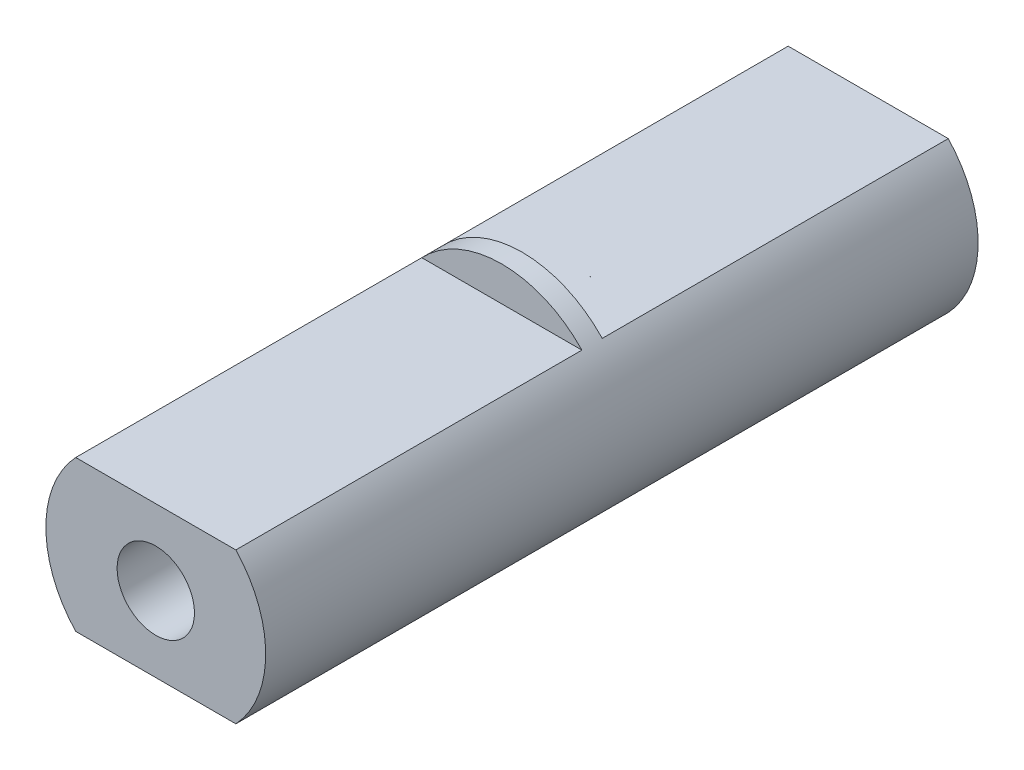
SolidWorks part; units mm, degrees
ref_plane "Front Plane" through (0, 0, 0) normal (0, 0, 1) x (1, 0, 0)
ref_plane "Top Plane" through (0, 0, 0) normal (0, 1, 0) x (1, 0, 0)
ref_plane "Right Plane" through (0, 0, 0) normal (1, 0, 0) x (0, 0, -1)
sketch "Sketch2" plane through (0, 0, 0) normal (0, 0, 1) x (1, 0, 0)
  line L0 (0, 1.85) -> (0, -1.85)
  line L1 (-1.9666, 1.85) -> (1.9666, 1.85)
  line L2 (1.9666, -1.85) -> (-1.9666, -1.85)
  arc A0 (-1.9666, 1.85) -> (-1.9666, -1.85) centre (0, 0) ccw
  circle A1 centre (0, 0) radius 0.95
  arc A2 (1.9666, -1.85) -> (1.9666, 1.85) centre (0, 0) ccw
extrude "Boss-Extrude2" add sketch "Sketch2" along normal blind 8.5 contours A1 L0 L1 A0 L2 | L2 A2 L1 L0 A1
sketch "Sketch3" plane through (0, 0, 0) normal (0, 0, -1) x (-1, 0, 0)
  circle A0 centre (0, 0) radius 2.7
  circle A1 centre (0, 0) radius 0.95
extrude "Boss-Extrude4" add sketch "Sketch3" along normal blind 9
sketch "Sketch4" plane through (0, 0, -9) normal (0, 0, -1) x (-1, 0, 0)
  line L0 (-1.9666, 1.85) -> (1.9666, 1.85)
  line L1 (1.9666, -1.85) -> (-1.9666, -1.85)
  circle A0 centre (0, 0) radius 0.95
  arc A1 (-1.9666, -1.85) -> (1.9666, -1.85) centre (0, 0) ccw
  arc A2 (1.9666, 1.85) -> (-1.9666, 1.85) centre (0, 0) ccw
extrude "Cut-Extrude1" cut sketch "Sketch4" against normal blind 8.5
